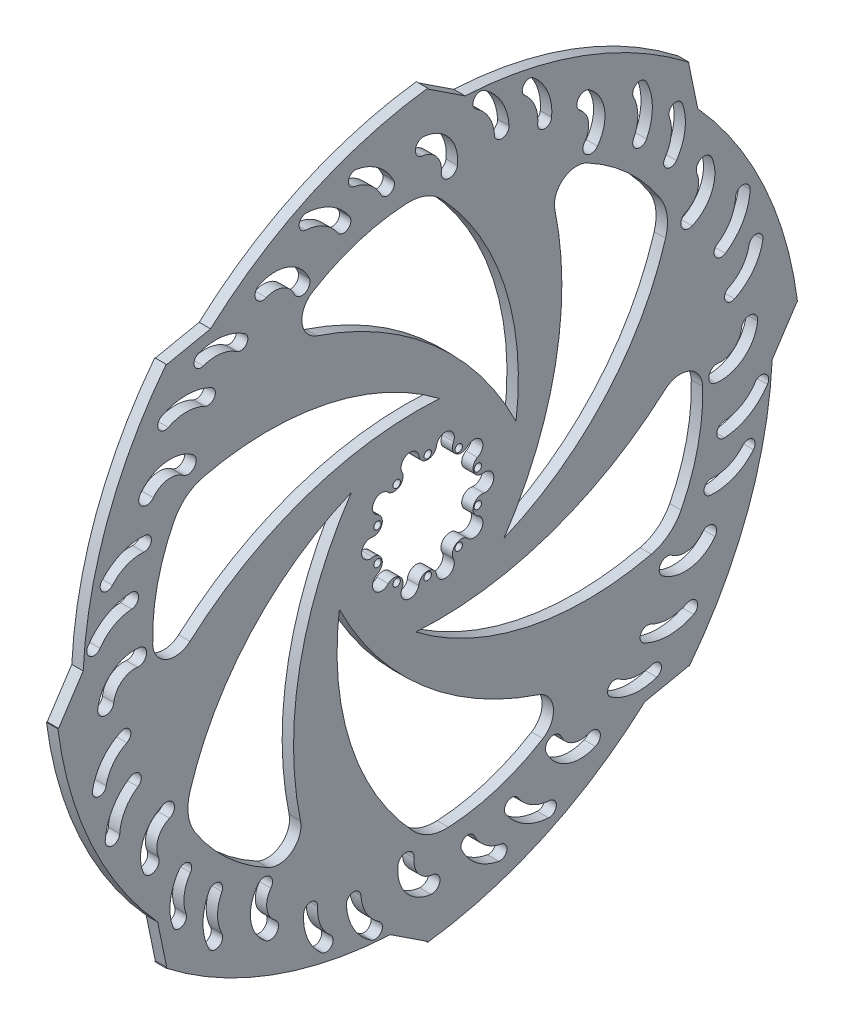
SolidWorks part; units mm, degrees
ref_plane "Front Plane" through (0, 0, 0) normal (0, 0, 1) x (1, 0, 0)
ref_plane "Top Plane" through (0, 0, 0) normal (0, 1, 0) x (1, 0, 0)
ref_plane "Right Plane" through (0, 0, 0) normal (1, 0, 0) x (0, 0, -1)
sketch "Sketch1" plane through (0, 0, 0) normal (1, 0, 0) x (0, 0, -1)
  circle A0 centre (0, 0) radius 82.55
  dimension "D1" = 165.1
extrude "Boss-Extrude2" add sketch "Sketch1" along normal blind 2.54 contours A0
sketch "Sketch3" plane through (2.54, 0, 0) normal (1, 0, 0) x (0, 0, -1)
  circle A0 centre (0, 0) radius 12.75
  arc A1 (-1.9931, 12.5839) -> (1.9469, 12.2921) centre (0, 12.75) ccw
  arc A2 (5.7842, 11.3521) -> (1.9469, 12.2921) centre (3.94, 12.126) ccw
  arc A3 (5.7842, 11.3521) -> (9.009, 9.009) centre (7.4943, 10.315) ccw
  arc A4 (11.0889, 5.6501) -> (9.009, 9.009) centre (10.315, 7.4943) ccw
  arc A6 (12.5839, -1.9931) -> (12.5839, 1.9931) centre (12.75, 0) ccw
  arc A7 (12.5839, -1.9931) -> (11.3521, -5.7842) centre (12.126, -3.94) ccw
  arc A8 (8.8002, -8.8002) -> (11.3521, -5.7842) centre (10.315, -7.4943) ccw
  arc A10 (1.9469, -12.2921) -> (5.7842, -11.3521) centre (3.94, -12.126) ccw
  arc A12 (-5.6501, -11.0889) -> (-1.9931, -12.5839) centre (-3.94, -12.126) ccw
  arc A14 (-11.3521, -5.7842) -> (-8.8002, -8.8002) centre (-10.315, -7.4943) ccw
  arc A15 (-11.3521, -5.7842) -> (-12.2921, -1.9469) centre (-12.126, -3.94) ccw
  arc A16 (-12.5839, 1.9931) -> (-12.2921, -1.9469) centre (-12.75, 0) ccw
  arc A17 (-12.5839, 1.9931) -> (-11.0889, 5.6501) centre (-12.126, 3.94) ccw
  arc A18 (-9.009, 9.009) -> (-11.0889, 5.6501) centre (-10.315, 7.4943) ccw
  arc A19 (-9.009, 9.009) -> (-5.6501, 11.0889) centre (-7.4943, 10.315) ccw
  arc A20 (-1.9931, 12.5839) -> (-5.6501, 11.0889) centre (-3.94, 12.126) ccw
  arc A21 (-5.6501, -11.0889) -> (-8.8002, -8.8002) centre (-7.4943, -10.315) ccw
  arc A22 (1.9469, -12.2921) -> (-1.9931, -12.5839) centre (0, -12.75) ccw
  arc A23 (8.8002, -8.8002) -> (5.7842, -11.3521) centre (7.4943, -10.315) ccw
  circle A24 centre (0, 11.7769) radius 0.8284
  circle A25 centre (6.9223, 9.5277) radius 0.8284
  arc A26 (11.0889, 5.6501) -> (12.5839, 1.9931) centre (12.126, 3.94) ccw
  arc A27 (11.3607, 5.7877) -> (11.3521, 5.7842) centre (12.126, 3.94) ccw [skipped]
  arc A28 (-5.789, -11.36) -> (-5.7842, -11.3521) centre (-7.4943, -10.315) ccw [skipped]
  arc A29 (1.9938, -12.5931) -> (1.9931, -12.5839) centre (0, -12.75) ccw [skipped]
  arc A30 (9.0151, -9.0161) -> (9.009, -9.009) centre (7.4943, -10.315) ccw [skipped]
  circle A31 centre (11.2005, 3.6393) radius 0.8284
  circle A32 centre (11.2005, -3.6393) radius 0.8284
  circle A33 centre (6.9223, -9.5277) radius 0.8284
  circle A34 centre (0, -11.7769) radius 0.8284
  circle A35 centre (-6.9223, -9.5277) radius 0.8284
  circle A36 centre (-11.2005, -3.6393) radius 0.8284
  circle A37 centre (-11.2005, 3.6393) radius 0.8284
  circle A38 centre (-6.9223, 9.5277) radius 0.8284
  point P46 (0, 0)
  point P58 (0, 0)
  dimension "D1" = 25.5
  dimension "D2" = 4
  dimension "D3" = 20
  dimension "D4" = 10
extrude "Cut-Extrude2" cut sketch "Sketch3" against normal through all contours A37 | A36 | A35 | A34 | A33 | A32 | A31 | A25 | A24 | A26 A4 A0 A3 A2 A1 A20 A19 A18 A17 A16 A15 A14 A21 A12 A22 A10 A23 A8 A7 A6 | A38
sketch "Sketch4" plane through (2.54, 0, 0) normal (1, 0, 0) x (0, 0, -1)
  line L0 (0, 0) -> (116.7631, 0) construction
  line L1 (0, 0) -> (75.4777, 75.4777) construction
  line L2 (58.2559, 58.2559) -> (60.2782, 48.4669)
  line L3 (58.2559, 58.2559) -> (59.6994, 59.6994)
  line L4 (59.6994, 59.6994) -> (74.9291, 56.8737)
  line L5 (74.9291, 56.8737) -> (99.5147, 21.0868)
  line L6 (99.5147, 21.0868) -> (84.1991, 0)
  line L7 (84.1991, 0) -> (82.55, 0)
  arc A0 (82.55, 0) -> (60.2782, 48.4669) centre (-5.7744, -11.2367) ccw
  circle A1 centre (0, 0) radius 82.55 construction
  dimension "D1" = 45
extrude "Cut-Extrude4" cut sketch "Sketch4" against normal through all
pattern_circular "CirPattern1" count 8 over 360 about axis through (0, 0, 0) along (1, 0, 0) of "Cut-Extrude4"
sketch "Sketch5" plane through (2.54, 0, 0) normal (1, 0, 0) x (0, 0, -1)
  arc A0 (-25.7138, 56.0171) -> (-4.6542, 62.6242) centre (-2.3098, 18.2855) cw
  arc A1 (3.1683, 59.4786) -> (19.722, 8.304) centre (-42.8443, 16.33) cw
  arc A2 (-24.6601, 47.025) -> (19.722, 8.304) centre (-48.8449, -25.4917) cw
  arc A4 (3.1683, 59.4786) -> (-4.6542, 62.6242) centre (-4.1262, 52.6382) ccw
  arc A5 (-25.7138, 56.0171) -> (-24.6601, 47.025) centre (-23.0782, 51.7681) ccw
  circle A6 centre (0, 0) radius 128.5423
  circle A7 centre (0, 0) radius 128.5423
  arc A8 (28.3948, 44.8688) -> (17.0525, -12.9278) centre (-46.4989, 29.5551) cw
  arc A9 (35.6554, 50.2773) -> (28.3948, 44.8688) centre (33.2934, 45.8704) ccw
  arc A10 (35.6554, 50.2773) -> (51.9071, 35.3427) centre (14.6808, 11.1431) cw
  arc A11 (53.0941, 26.9955) -> (17.0525, -12.9278) centre (-7.28, 45.2692) cw
  arc A12 (53.0941, 26.9955) -> (51.9071, 35.3427) centre (43.5229, 29.8925) ccw
  circle A13 centre (0, 0) radius 128.5423
  arc A14 (53.0549, -2.1562) -> (-2.6695, -21.2318) centre (2.346, 55.0468) cw
  arc A15 (61.3691, -5.7398) -> (53.0549, -2.1562) centre (56.3716, -5.8977) ccw
  arc A16 (61.3691, -5.7398) -> (56.5612, -27.2815) centre (16.9906, -7.1424) cw
  arc A17 (49.9258, -32.4831) -> (-2.6695, -21.2318) centre (35.5643, 28.9393) cw
  arc A18 (49.9258, -32.4831) -> (56.5612, -27.2815) centre (47.6491, -22.7457) ccw
  circle A19 centre (0, 0) radius 128.5423
  arc A20 (24.6601, -47.025) -> (-19.722, -8.304) centre (48.8449, 25.4917) cw
  arc A21 (25.7138, -56.0171) -> (24.6601, -47.025) centre (23.0782, -51.7681) ccw
  arc A22 (25.7138, -56.0171) -> (4.6542, -62.6242) centre (2.3098, -18.2855) cw
  arc A23 (-3.1683, -59.4786) -> (-19.722, -8.304) centre (42.8443, -16.33) cw
  arc A24 (-3.1683, -59.4786) -> (4.6542, -62.6242) centre (4.1262, -52.6382) ccw
  circle A25 centre (0, 0) radius 128.5423
  arc A26 (-28.3948, -44.8688) -> (-17.0525, 12.9278) centre (46.4989, -29.5551) cw
  arc A27 (-35.6554, -50.2773) -> (-28.3948, -44.8688) centre (-33.2934, -45.8704) ccw
  arc A28 (-35.6554, -50.2773) -> (-51.9071, -35.3427) centre (-14.6808, -11.1431) cw
  arc A29 (-53.0941, -26.9955) -> (-17.0525, 12.9278) centre (7.28, -45.2692) cw
  arc A30 (-53.0941, -26.9955) -> (-51.9071, -35.3427) centre (-43.5229, -29.8925) ccw
  circle A31 centre (0, 0) radius 128.5423
  arc A32 (-53.0549, 2.1562) -> (2.6695, 21.2318) centre (-2.346, -55.0468) cw
  arc A33 (-61.3691, 5.7398) -> (-53.0549, 2.1562) centre (-56.3716, 5.8977) ccw
  arc A34 (-61.3691, 5.7398) -> (-56.5612, 27.2815) centre (-16.9906, 7.1424) cw
  arc A35 (-49.9258, 32.4831) -> (2.6695, 21.2318) centre (-35.5643, -28.9393) cw
  arc A36 (-49.9258, 32.4831) -> (-56.5612, 27.2815) centre (-47.6491, 22.7457) ccw
  point P70 (0, 0)
  dimension "D1" = 10
  dimension "D2" = 5
  dimension "D3" = 6
extrude "Cut-Extrude6" cut sketch "Sketch5" against normal through all contours A17 A18 A16 A15 A14 | A1 A2 A5 A0 A4 | A8 A11 A12 A10 A9 | A20 A23 A24 A22 A21 | A26 A29 A30 A28 A27 | A32 A35 A36 A34 A33
sketch "Sketch6" plane through (2.54, 0, 0) normal (1, 0, 0) x (0, 0, -1)
  arc A0 (35.1112, 62.6875) -> (36.4579, 53.4856) centre (31.1836, 57.4132) cw construction
  arc A1 (37.9098, 52.4043) -> (36.1925, 64.1394) centre (31.1836, 57.4132) ccw
  arc A2 (35.0059, 54.5668) -> (34.03, 61.2355) centre (31.1836, 57.4132) ccw
  arc A3 (35.0059, 54.5668) -> (37.9098, 52.4043) centre (36.4579, 53.4856) ccw
  arc A4 (36.1925, 64.1394) -> (34.03, 61.2355) centre (35.1112, 62.6875) ccw
  arc A5 (47.3886, 58.6275) -> (47.3886, 49.0283) centre (37.858, 53.8279) cw construction
  arc A6 (48.8424, 48.2961) -> (48.8424, 59.3597) centre (37.858, 53.8279) ccw
  arc A7 (45.9347, 49.7604) -> (45.9347, 57.8954) centre (37.858, 53.8279) ccw
  arc A8 (45.9347, 49.7604) -> (48.8424, 48.2961) centre (47.3886, 49.0283) ccw
  arc A9 (48.8424, 59.3597) -> (45.9347, 57.8954) centre (47.3886, 58.6275) ccw
  arc A10 (55.3949, 50.6152) -> (54.2363, 41.7028) centre (46.0688, 47.2961) cw construction
  arc A11 (55.526, 40.8196) -> (56.8676, 51.1394) centre (46.0688, 47.2961) ccw
  arc A12 (52.9465, 42.5861) -> (53.9222, 50.0911) centre (46.0688, 47.2961) ccw
  arc A13 (52.9465, 42.5861) -> (55.526, 40.8196) centre (54.2363, 41.7028) ccw
  arc A14 (56.8676, 51.1394) -> (53.9222, 50.0911) centre (55.3949, 50.6152) ccw
  circle A15 centre (0, 0) radius 123.926
  arc A20 (57.5994, 29.7533) -> (60.0885, 36.0165) centre (55.7124, 34.1295) ccw
  circle A25 centre (0, 0) radius 123.926
  arc A26 (57.5994, 29.7533) -> (59.033, 26.4285) centre (58.3162, 28.0909) ccw
  arc A27 (63.4134, 37.4501) -> (60.0885, 36.0165) centre (61.751, 36.7333) ccw
  arc A28 (59.033, 26.4285) -> (63.4134, 37.4501) centre (55.7124, 34.1295) ccw
  arc A29 (64.6609, 20.1264) -> (68.7284, 27.1715) centre (59.7, 27.6873) ccw
  arc A30 (64.6609, 20.1264) -> (66.4468, 17.4045) centre (65.5538, 18.7655) ccw
  arc A31 (71.9786, 26.9858) -> (68.7284, 27.1715) centre (70.3535, 27.0787) ccw
  arc A32 (66.4468, 17.4045) -> (71.9786, 26.9858) centre (59.7, 27.6873) ccw
  arc A33 (67.1461, 10.4074) -> (71.7435, 16.4191) centre (63.5448, 17.9253) ccw
  arc A34 (67.1461, 10.4074) -> (68.4967, 7.5878) centre (67.8214, 8.9976) ccw
  arc A35 (74.8185, 15.8542) -> (71.7435, 16.4191) centre (73.281, 16.1366) ccw
  arc A36 (68.4967, 7.5878) -> (74.8185, 15.8542) centre (63.5448, 17.9253) ccw
  arc A37 (61.751, 36.7333) -> (58.3162, 28.0909) centre (55.7124, 34.1295) cw construction
  arc A38 (70.3535, 27.0787) -> (65.5538, 18.7655) centre (59.7, 27.6873) cw construction
  arc A39 (73.281, 16.1366) -> (67.8214, 8.9976) centre (63.5448, 17.9253) cw construction
  circle A40 centre (0, 0) radius 123.926
  arc A41 (64.7592, -3.0326) -> (70.0465, 1.1469) centre (65.3131, 1.7008) ccw
  arc A42 (64.7592, -3.0326) -> (64.3384, -6.6287) centre (64.5488, -4.8306) ccw
  arc A43 (73.6426, 0.7261) -> (70.0465, 1.1469) centre (71.8445, 0.9365) ccw
  arc A44 (64.3384, -6.6287) -> (73.6426, 0.7261) centre (65.3131, 1.7008) ccw
  arc A45 (66.0612, -14.9004) -> (73.1063, -10.833) centre (65.5453, -5.872) ccw
  arc A46 (66.0612, -14.9004) -> (66.2469, -18.1507) centre (66.154, -16.5256) ccw
  arc A47 (75.8282, -12.6189) -> (73.1063, -10.833) centre (74.4672, -11.7259) ccw
  arc A48 (66.2469, -18.1507) -> (75.8282, -12.6189) centre (65.5453, -5.872) ccw
  arc A49 (63.3539, -24.56) -> (70.3413, -21.6524) centre (63.994, -16.2487) ccw
  arc A50 (63.3539, -24.56) -> (63.1138, -27.6772) centre (63.2338, -26.1186) ccw
  arc A51 (72.7218, -23.6791) -> (70.3413, -21.6524) centre (71.5315, -22.6658) ccw
  arc A52 (63.1138, -27.6772) -> (72.7218, -23.6791) centre (63.994, -16.2487) ccw
  arc A53 (71.8445, 0.9365) -> (64.5488, -4.8306) centre (65.3131, 1.7008) cw construction
  arc A54 (74.4672, -11.7259) -> (66.154, -16.5256) centre (65.5453, -5.872) cw construction
  arc A55 (71.5315, -22.6658) -> (63.2338, -26.1186) centre (63.994, -16.2487) cw construction
  circle A56 centre (0, 0) radius 123.926
  arc A57 (54.5668, -35.0059) -> (61.2355, -34.03) centre (57.4132, -31.1836) ccw
  arc A58 (54.5668, -35.0059) -> (52.4043, -37.9098) centre (53.4856, -36.4579) ccw
  arc A59 (64.1394, -36.1925) -> (61.2355, -34.03) centre (62.6875, -35.1112) ccw
  arc A60 (52.4043, -37.9098) -> (64.1394, -36.1925) centre (57.4132, -31.1836) ccw
  arc A61 (49.7604, -45.9347) -> (57.8954, -45.9347) centre (53.8279, -37.858) ccw
  arc A62 (49.7604, -45.9347) -> (48.2961, -48.8424) centre (49.0283, -47.3886) ccw
  arc A63 (59.3597, -48.8424) -> (57.8954, -45.9347) centre (58.6275, -47.3886) ccw
  arc A64 (48.2961, -48.8424) -> (59.3597, -48.8424) centre (53.8279, -37.858) ccw
  arc A65 (42.5861, -52.9465) -> (50.0911, -53.9222) centre (47.2961, -46.0688) ccw
  arc A66 (42.5861, -52.9465) -> (40.8196, -55.526) centre (41.7028, -54.2363) ccw
  arc A67 (51.1394, -56.8676) -> (50.0911, -53.9222) centre (50.6152, -55.3949) ccw
  arc A68 (40.8196, -55.526) -> (51.1394, -56.8676) centre (47.2961, -46.0688) ccw
  arc A69 (62.6875, -35.1112) -> (53.4856, -36.4579) centre (57.4132, -31.1836) cw construction
  arc A70 (58.6275, -47.3886) -> (49.0283, -47.3886) centre (53.8279, -37.858) cw construction
  arc A71 (50.6152, -55.3949) -> (41.7028, -54.2363) centre (47.2961, -46.0688) cw construction
  circle A72 centre (0, 0) radius 123.926
  arc A73 (29.7533, -57.5994) -> (36.0165, -60.0885) centre (34.1295, -55.7124) ccw
  arc A74 (29.7533, -57.5994) -> (26.4285, -59.033) centre (28.0909, -58.3162) ccw
  arc A75 (37.4501, -63.4134) -> (36.0165, -60.0885) centre (36.7333, -61.751) ccw
  arc A76 (26.4285, -59.033) -> (37.4501, -63.4134) centre (34.1295, -55.7124) ccw
  arc A77 (20.1264, -64.6609) -> (27.1715, -68.7284) centre (27.6873, -59.7) ccw
  arc A78 (20.1264, -64.6609) -> (17.4045, -66.4468) centre (18.7655, -65.5538) ccw
  arc A79 (26.9858, -71.9786) -> (27.1715, -68.7284) centre (27.0787, -70.3535) ccw
  arc A80 (17.4045, -66.4468) -> (26.9858, -71.9786) centre (27.6873, -59.7) ccw
  arc A81 (10.4074, -67.1461) -> (16.4191, -71.7435) centre (17.9253, -63.5448) ccw
  arc A82 (10.4074, -67.1461) -> (7.5878, -68.4967) centre (8.9976, -67.8214) ccw
  arc A83 (15.8542, -74.8185) -> (16.4191, -71.7435) centre (16.1366, -73.281) ccw
  arc A84 (7.5878, -68.4967) -> (15.8542, -74.8185) centre (17.9253, -63.5448) ccw
  arc A85 (36.7333, -61.751) -> (28.0909, -58.3162) centre (34.1295, -55.7124) cw construction
  arc A86 (27.0787, -70.3535) -> (18.7655, -65.5538) centre (27.6873, -59.7) cw construction
  arc A87 (16.1366, -73.281) -> (8.9976, -67.8214) centre (17.9253, -63.5448) cw construction
  circle A88 centre (0, 0) radius 123.926
  arc A89 (-3.0326, -64.7592) -> (1.1469, -70.0465) centre (1.7008, -65.3131) ccw
  arc A90 (-3.0326, -64.7592) -> (-6.6287, -64.3384) centre (-4.8306, -64.5488) ccw
  arc A91 (0.7261, -73.6426) -> (1.1469, -70.0465) centre (0.9365, -71.8445) ccw
  arc A92 (-6.6287, -64.3384) -> (0.7261, -73.6426) centre (1.7008, -65.3131) ccw
  arc A93 (-14.9004, -66.0612) -> (-10.833, -73.1063) centre (-5.872, -65.5453) ccw
  arc A94 (-14.9004, -66.0612) -> (-18.1507, -66.2469) centre (-16.5256, -66.154) ccw
  arc A95 (-12.6189, -75.8282) -> (-10.833, -73.1063) centre (-11.7259, -74.4672) ccw
  arc A96 (-18.1507, -66.2469) -> (-12.6189, -75.8282) centre (-5.872, -65.5453) ccw
  arc A97 (-24.56, -63.3539) -> (-21.6524, -70.3413) centre (-16.2487, -63.994) ccw
  arc A98 (-24.56, -63.3539) -> (-27.6772, -63.1138) centre (-26.1186, -63.2338) ccw
  arc A99 (-23.6791, -72.7218) -> (-21.6524, -70.3413) centre (-22.6658, -71.5315) ccw
  arc A100 (-27.6772, -63.1138) -> (-23.6791, -72.7218) centre (-16.2487, -63.994) ccw
  arc A101 (0.9365, -71.8445) -> (-4.8306, -64.5488) centre (1.7008, -65.3131) cw construction
  arc A102 (-11.7259, -74.4672) -> (-16.5256, -66.154) centre (-5.872, -65.5453) cw construction
  arc A103 (-22.6658, -71.5315) -> (-26.1186, -63.2338) centre (-16.2487, -63.994) cw construction
  circle A104 centre (0, 0) radius 123.926
  arc A105 (-35.0059, -54.5668) -> (-34.03, -61.2355) centre (-31.1836, -57.4132) ccw
  arc A106 (-35.0059, -54.5668) -> (-37.9098, -52.4043) centre (-36.4579, -53.4856) ccw
  arc A107 (-36.1925, -64.1394) -> (-34.03, -61.2355) centre (-35.1112, -62.6875) ccw
  arc A108 (-37.9098, -52.4043) -> (-36.1925, -64.1394) centre (-31.1836, -57.4132) ccw
  arc A109 (-45.9347, -49.7604) -> (-45.9347, -57.8954) centre (-37.858, -53.8279) ccw
  arc A110 (-45.9347, -49.7604) -> (-48.8424, -48.2961) centre (-47.3886, -49.0283) ccw
  arc A111 (-48.8424, -59.3597) -> (-45.9347, -57.8954) centre (-47.3886, -58.6275) ccw
  arc A112 (-48.8424, -48.2961) -> (-48.8424, -59.3597) centre (-37.858, -53.8279) ccw
  arc A113 (-52.9465, -42.5861) -> (-53.9222, -50.0911) centre (-46.0688, -47.2961) ccw
  arc A114 (-52.9465, -42.5861) -> (-55.526, -40.8196) centre (-54.2363, -41.7028) ccw
  arc A115 (-56.8676, -51.1394) -> (-53.9222, -50.0911) centre (-55.3949, -50.6152) ccw
  arc A116 (-55.526, -40.8196) -> (-56.8676, -51.1394) centre (-46.0688, -47.2961) ccw
  arc A117 (-35.1112, -62.6875) -> (-36.4579, -53.4856) centre (-31.1836, -57.4132) cw construction
  arc A118 (-47.3886, -58.6275) -> (-47.3886, -49.0283) centre (-37.858, -53.8279) cw construction
  arc A119 (-55.3949, -50.6152) -> (-54.2363, -41.7028) centre (-46.0688, -47.2961) cw construction
  circle A120 centre (0, 0) radius 123.926
  arc A121 (-57.5994, -29.7533) -> (-60.0885, -36.0165) centre (-55.7124, -34.1295) ccw
  arc A122 (-57.5994, -29.7533) -> (-59.033, -26.4285) centre (-58.3162, -28.0909) ccw
  arc A123 (-63.4134, -37.4501) -> (-60.0885, -36.0165) centre (-61.751, -36.7333) ccw
  arc A124 (-59.033, -26.4285) -> (-63.4134, -37.4501) centre (-55.7124, -34.1295) ccw
  arc A125 (-64.6609, -20.1264) -> (-68.7284, -27.1715) centre (-59.7, -27.6873) ccw
  arc A126 (-64.6609, -20.1264) -> (-66.4468, -17.4045) centre (-65.5538, -18.7655) ccw
  arc A127 (-71.9786, -26.9858) -> (-68.7284, -27.1715) centre (-70.3535, -27.0787) ccw
  arc A128 (-66.4468, -17.4045) -> (-71.9786, -26.9858) centre (-59.7, -27.6873) ccw
  arc A129 (-67.1461, -10.4074) -> (-71.7435, -16.4191) centre (-63.5448, -17.9253) ccw
  arc A130 (-67.1461, -10.4074) -> (-68.4967, -7.5878) centre (-67.8214, -8.9976) ccw
  arc A131 (-74.8185, -15.8542) -> (-71.7435, -16.4191) centre (-73.281, -16.1366) ccw
  arc A132 (-68.4967, -7.5878) -> (-74.8185, -15.8542) centre (-63.5448, -17.9253) ccw
  arc A133 (-61.751, -36.7333) -> (-58.3162, -28.0909) centre (-55.7124, -34.1295) cw construction
  arc A134 (-70.3535, -27.0787) -> (-65.5538, -18.7655) centre (-59.7, -27.6873) cw construction
  arc A135 (-73.281, -16.1366) -> (-67.8214, -8.9976) centre (-63.5448, -17.9253) cw construction
  circle A136 centre (0, 0) radius 123.926
  arc A137 (-64.7592, 3.0326) -> (-70.0465, -1.1469) centre (-65.3131, -1.7008) ccw
  arc A138 (-64.7592, 3.0326) -> (-64.3384, 6.6287) centre (-64.5488, 4.8306) ccw
  arc A139 (-73.6426, -0.7261) -> (-70.0465, -1.1469) centre (-71.8445, -0.9365) ccw
  arc A140 (-64.3384, 6.6287) -> (-73.6426, -0.7261) centre (-65.3131, -1.7008) ccw
  arc A141 (-66.0612, 14.9004) -> (-73.1063, 10.833) centre (-65.5453, 5.872) ccw
  arc A142 (-66.0612, 14.9004) -> (-66.2469, 18.1507) centre (-66.154, 16.5256) ccw
  arc A143 (-75.8282, 12.6189) -> (-73.1063, 10.833) centre (-74.4672, 11.7259) ccw
  arc A144 (-66.2469, 18.1507) -> (-75.8282, 12.6189) centre (-65.5453, 5.872) ccw
  arc A145 (-63.3539, 24.56) -> (-70.3413, 21.6524) centre (-63.994, 16.2487) ccw
  arc A146 (-63.3539, 24.56) -> (-63.1138, 27.6772) centre (-63.2338, 26.1186) ccw
  arc A147 (-72.7218, 23.6791) -> (-70.3413, 21.6524) centre (-71.5315, 22.6658) ccw
  arc A148 (-63.1138, 27.6772) -> (-72.7218, 23.6791) centre (-63.994, 16.2487) ccw
  arc A149 (-71.8445, -0.9365) -> (-64.5488, 4.8306) centre (-65.3131, -1.7008) cw construction
  arc A150 (-74.4672, 11.7259) -> (-66.154, 16.5256) centre (-65.5453, 5.872) cw construction
  arc A151 (-71.5315, 22.6658) -> (-63.2338, 26.1186) centre (-63.994, 16.2487) cw construction
  circle A152 centre (0, 0) radius 123.926
  arc A153 (-54.5668, 35.0059) -> (-61.2355, 34.03) centre (-57.4132, 31.1836) ccw
  arc A154 (-54.5668, 35.0059) -> (-52.4043, 37.9098) centre (-53.4856, 36.4579) ccw
  arc A155 (-64.1394, 36.1925) -> (-61.2355, 34.03) centre (-62.6875, 35.1112) ccw
  arc A156 (-52.4043, 37.9098) -> (-64.1394, 36.1925) centre (-57.4132, 31.1836) ccw
  arc A157 (-49.7604, 45.9347) -> (-57.8954, 45.9347) centre (-53.8279, 37.858) ccw
  arc A158 (-49.7604, 45.9347) -> (-48.2961, 48.8424) centre (-49.0283, 47.3886) ccw
  arc A159 (-59.3597, 48.8424) -> (-57.8954, 45.9347) centre (-58.6275, 47.3886) ccw
  arc A160 (-48.2961, 48.8424) -> (-59.3597, 48.8424) centre (-53.8279, 37.858) ccw
  arc A161 (-42.5861, 52.9465) -> (-50.0911, 53.9222) centre (-47.2961, 46.0688) ccw
  arc A162 (-42.5861, 52.9465) -> (-40.8196, 55.526) centre (-41.7028, 54.2363) ccw
  arc A163 (-51.1394, 56.8676) -> (-50.0911, 53.9222) centre (-50.6152, 55.3949) ccw
  arc A164 (-40.8196, 55.526) -> (-51.1394, 56.8676) centre (-47.2961, 46.0688) ccw
  arc A165 (-62.6875, 35.1112) -> (-53.4856, 36.4579) centre (-57.4132, 31.1836) cw construction
  arc A166 (-58.6275, 47.3886) -> (-49.0283, 47.3886) centre (-53.8279, 37.858) cw construction
  arc A167 (-50.6152, 55.3949) -> (-41.7028, 54.2363) centre (-47.2961, 46.0688) cw construction
  circle A168 centre (0, 0) radius 123.926
  arc A169 (-29.7533, 57.5994) -> (-36.0165, 60.0885) centre (-34.1295, 55.7124) ccw
  arc A170 (-29.7533, 57.5994) -> (-26.4285, 59.033) centre (-28.0909, 58.3162) ccw
  arc A171 (-37.4501, 63.4134) -> (-36.0165, 60.0885) centre (-36.7333, 61.751) ccw
  arc A172 (-26.4285, 59.033) -> (-37.4501, 63.4134) centre (-34.1295, 55.7124) ccw
  arc A173 (-20.1264, 64.6609) -> (-27.1715, 68.7284) centre (-27.6873, 59.7) ccw
  arc A174 (-20.1264, 64.6609) -> (-17.4045, 66.4468) centre (-18.7655, 65.5538) ccw
  arc A175 (-26.9858, 71.9786) -> (-27.1715, 68.7284) centre (-27.0787, 70.3535) ccw
  arc A176 (-17.4045, 66.4468) -> (-26.9858, 71.9786) centre (-27.6873, 59.7) ccw
  arc A177 (-10.4074, 67.1461) -> (-16.4191, 71.7435) centre (-17.9253, 63.5448) ccw
  arc A178 (-10.4074, 67.1461) -> (-7.5878, 68.4967) centre (-8.9976, 67.8214) ccw
  arc A179 (-15.8542, 74.8185) -> (-16.4191, 71.7435) centre (-16.1366, 73.281) ccw
  arc A180 (-7.5878, 68.4967) -> (-15.8542, 74.8185) centre (-17.9253, 63.5448) ccw
  arc A181 (-36.7333, 61.751) -> (-28.0909, 58.3162) centre (-34.1295, 55.7124) cw construction
  arc A182 (-27.0787, 70.3535) -> (-18.7655, 65.5538) centre (-27.6873, 59.7) cw construction
  arc A183 (-16.1366, 73.281) -> (-8.9976, 67.8214) centre (-17.9253, 63.5448) cw construction
  circle A184 centre (0, 0) radius 123.926
  arc A185 (3.0326, 64.7592) -> (-1.1469, 70.0465) centre (-1.7008, 65.3131) ccw
  arc A186 (3.0326, 64.7592) -> (6.6287, 64.3384) centre (4.8306, 64.5488) ccw
  arc A187 (-0.7261, 73.6426) -> (-1.1469, 70.0465) centre (-0.9365, 71.8445) ccw
  arc A188 (6.6287, 64.3384) -> (-0.7261, 73.6426) centre (-1.7008, 65.3131) ccw
  arc A189 (14.9004, 66.0612) -> (10.833, 73.1063) centre (5.872, 65.5453) ccw
  arc A190 (14.9004, 66.0612) -> (18.1507, 66.2469) centre (16.5256, 66.154) ccw
  arc A191 (12.6189, 75.8282) -> (10.833, 73.1063) centre (11.7259, 74.4672) ccw
  arc A192 (18.1507, 66.2469) -> (12.6189, 75.8282) centre (5.872, 65.5453) ccw
  arc A193 (24.56, 63.3539) -> (21.6524, 70.3413) centre (16.2487, 63.994) ccw
  arc A194 (24.56, 63.3539) -> (27.6772, 63.1138) centre (26.1186, 63.2338) ccw
  arc A195 (23.6791, 72.7218) -> (21.6524, 70.3413) centre (22.6658, 71.5315) ccw
  arc A196 (27.6772, 63.1138) -> (23.6791, 72.7218) centre (16.2487, 63.994) ccw
  arc A197 (-0.9365, 71.8445) -> (4.8306, 64.5488) centre (-1.7008, 65.3131) cw construction
  arc A198 (11.7259, 74.4672) -> (16.5256, 66.154) centre (5.872, 65.5453) cw construction
  arc A199 (22.6658, 71.5315) -> (26.1186, 63.2338) centre (16.2487, 63.994) cw construction
  point P3 (37.6903, 58.3654)
  point P8 (48.5289, 53.8279)
  point P16 (55.8853, 46.02)
  point P24 (0, 0)
  point P30 (61.8235, 31.7008)
  point P35 (68.9412, 22.3519)
  point P46 (71.4081, 11.9118)
  point P58 (69.3911, -3.4581)
  point P63 (70.8808, -15.1133)
  point P71 (67.7971, -25.3881)
  point P83 (58.3654, -37.6903)
  point P88 (53.8279, -48.5289)
  point P96 (46.02, -55.8853)
  point P108 (31.7008, -61.8235)
  point P113 (22.3519, -68.9412)
  point P121 (11.9118, -71.4081)
  point P133 (-3.4581, -69.3911)
  point P138 (-15.1133, -70.8808)
  point P146 (-25.3881, -67.7971)
  point P158 (-37.6903, -58.3654)
  point P163 (-48.5289, -53.8279)
  point P171 (-55.8853, -46.02)
  point P183 (-61.8235, -31.7008)
  point P188 (-68.9412, -22.3519)
  point P196 (-71.4081, -11.9118)
  point P208 (-69.3911, 3.4581)
  point P213 (-70.8808, 15.1133)
  point P221 (-67.7971, 25.3881)
  point P233 (-58.3654, 37.6903)
  point P238 (-53.8279, 48.5289)
  point P246 (-46.02, 55.8853)
  point P258 (-31.7008, 61.8235)
  point P263 (-22.3519, 68.9412)
  point P271 (-11.9118, 71.4081)
  point P283 (3.4581, 69.3911)
  point P288 (15.1133, 70.8808)
  point P296 (25.3881, 67.7971)
  point P305 (0, 0)
  dimension "D1" = 12
extrude "Cut-Extrude8" cut sketch "Sketch6" against normal blind 10 contours A42 A44 A43 A41 | A34 A36 A35 A33 | A30 A32 A31 A29 | A26 A28 A27 A20 | A11 A14 A12 A13 | A6 A9 A7 A8 | A1 A4 A2 A3 | A190 A192 A191 A189 | A186 A188 A187 A185 | A178 A180 A179 A177 | A174 A176 A175 A173 | A170 A172 A171 A169 | A162 A164 A163 A161 | A158 A160 A159 A157 | A154 A156 A155 A153 | A146 A148 A147 A145 | A142 A144 A143 A141 | A138 A140 A139 A137 | A130 A132 A131 A129 | A126 A128 A127 A125 | A122 A124 A123 A121 | A114 A116 A115 A113 | A110 A112 A111 A109 | A106 A108 A107 A105 | A98 A100 A99 A97 | A94 A96 A95 A93 | A90 A92 A91 A89 | A82 A84 A83 A81 | A78 A80 A79 A77 | A74 A76 A75 A73 | A66 A68 A67 A65 | A47 A45 A46 A48 | A196 A195 A193 A194 | A60 A59 A57 A58 | A61 A63 A64 A62 | A49 A51 A52 A50
